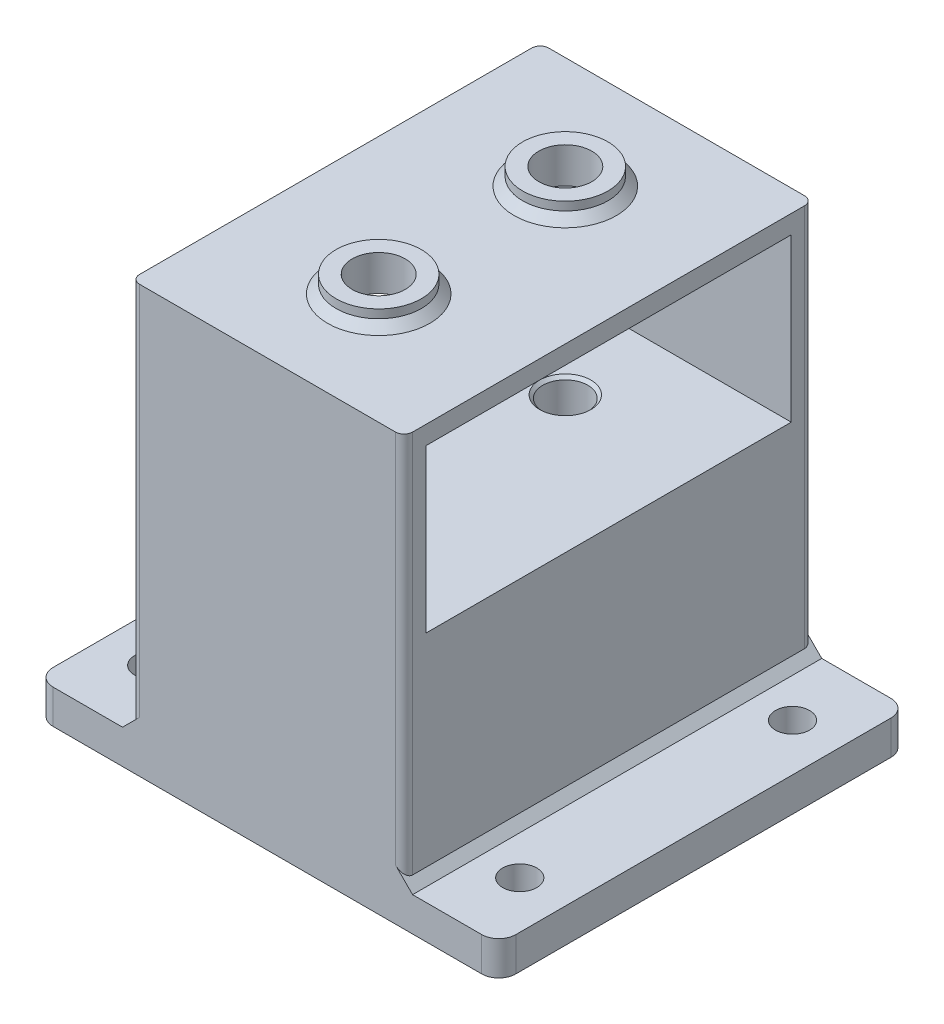
SolidWorks part; units mm, degrees
ref_plane "前视基准面" through (0, 0, 0) normal (0, 0, 1) x (1, 0, 0)
ref_plane "上视基准面" through (0, 0, 0) normal (0, 1, 0) x (1, 0, 0)
ref_plane "右视基准面" through (0, 0, 0) normal (1, 0, 0) x (0, 0, -1)
other "Configuration Table"
sketch "草图1" plane through (0, 370, 0) normal (0, 1, 0) x (1, 0, 0)
  line L1 (-1100, 120) -> (-878.5828, 120)
  line L2 (-1100, 120) -> (-1100, -120)
  line L3 (-1100, -120) -> (-878.5828, -120)
  line L4 (-878.5828, 120) -> (-878.5828, -120)
extrude "凸台-拉伸1" add sketch "草图1" along normal up to surface (20 mm away)
sketch "草图2" plane through (0, 390, 0) normal (0, 1, 0) x (1, 0, 0)
  line L0 (-878.5828, 120) -> (-1100, 120) construction
  line L1 (-1069.2914, 120) -> (-909.1384, 120)
  line L2 (-1069.2914, 120) -> (-1069.2914, -120)
  line L3 (-1069.2914, -120) -> (-909.1384, -120)
  line L4 (-909.1384, 120) -> (-909.1384, -120)
  line L5 (-1069.2914, 120) -> (-1069.2914, -120) construction
  line L6 (-1100, -120) -> (-878.5828, -120) construction
extrude "凸台-拉伸2" add sketch "草图2" along normal up to surface (230 mm away)
sketch "草图3" plane through (-1069.2914, 0, 0) normal (-1, 0, 0) x (0, 0, 1)
  line L1 (-107.105, 609.15) -> (107.105, 609.15)
  line L2 (-107.105, 609.15) -> (-107.105, 513.97)
  line L3 (-107.105, 513.97) -> (107.105, 513.97)
  line L4 (107.105, 609.15) -> (107.105, 513.97)
extrude "切除-拉伸1" cut sketch "草图3" against normal through all
sketch "草图4" plane through (0, 513.97, 0) normal (0, 1, 0) x (1, 0, 0)
  circle A0 centre (-989.2914, 54.73) radius 15.5621
  circle A1 centre (-989.2914, -54.73) radius 15.5621
  point P7 (-989.2914, 54.73)
  point P8 (-989.2914, -54.73)
hole_wizard "M30 螺纹孔1" positions "草图8" profile "草图10" tap size "M30" standard "GB"
sketch "草图8" plane through (0, 513.97, 0) normal (0, 1, 0) x (1, 0, 0)
  point P0 (-989.2914, 54.73)
  point P4 (-989.2914, -54.73)
sketch "草图10" plane through (-989.2914, 513.97, -54.73) normal (1, 0, 0) x (0, 0, 1)
  line L0 (0, 0) -> (0, 57.9614)
  line L1 (0, 57.9614) -> (13.25, 50)
  line L2 (13.25, 50) -> (13.25, 1.775)
  line L3 (13.25, 1.775) -> (15.025, 0)
  line L5 (15.025, 0) -> (0, 0)
  line L6 (-13.25, 1.775) -> (-15.025, 0) construction
  line L10 (0, 57.9614) -> (-13.25, 50) construction
  line L11 (0, -6.35) -> (0, 107.95) construction
  dimension "螺纹孔钻头直径" = 26.5
  dimension "螺纹孔钻头深度" = 50
  dimension "近端锥形沉头孔直径" = 30.05
  dimension "近端锥形沉头孔角度" = 90
  dimension "导头角度" = 118
cosmetic thread "孔螺蚊线1" parameters "D1"=50, "D2"=30
cosmetic thread "孔螺蚊线2" parameters "D1"=50, "D2"=30
sketch "草图11" plane through (0, 620, 0) normal (0, 1, 0) x (1, 0, 0)
  circle A0 centre (-989.2914, 54.73) radius 15.5621
  circle A1 centre (-989.2914, -54.73) radius 15.5621
extrude "切除-拉伸3" cut sketch "草图11" against normal blind 20
sketch "草图12" plane through (0, 620, 0) normal (0, 1, 0) x (1, 0, 0)
  circle A0 centre (-989.2914, 54.73) radius 25
  circle A1 centre (-989.2914, -54.73) radius 25
  dimension "D1" = 50
  dimension "D2" = 50
extrude "凸台-拉伸3" add sketch "草图12" along normal blind 10
sketch "草图13" plane through (0, 630, 0) normal (0, 1, 0) x (1, 0, 0)
  circle A0 centre (-989.2914, 54.73) radius 15.5621
  circle A1 centre (-989.2914, -54.73) radius 15.5621
extrude "切除-拉伸4" cut sketch "草图13" along normal mid plane 59
sketch "草图14" plane through (0, 370, 0) normal (0, -1, 0) x (1, 0, 0)
  line L0 (-878.5828, -120) -> (-1100, -120) construction
  line L1 (-1100, 120) -> (-1125, 120)
  line L2 (-1100, 120) -> (-1100, -120)
  line L3 (-1100, -120) -> (-1125, -120)
  line L4 (-1125, 120) -> (-1125, -120)
  line L5 (-1100, 120) -> (-878.5828, 120) construction
  line L6 (-878.5828, 120) -> (-853.5828, 120)
  line L7 (-878.5828, 120) -> (-878.5828, -120)
  line L8 (-878.5828, -120) -> (-853.5828, -120)
  line L9 (-853.5828, 120) -> (-853.5828, -120)
  line L10 (-878.5828, 120) -> (-878.5828, -120) construction
  dimension "D1" = 25
  dimension "D2" = 25
extrude "凸台-拉伸4" add sketch "草图14" against normal up to surface (20 mm away) up to face at (-1084.6457, 390, 0)
sketch "草图15" plane through (0, 390, 0) normal (0, 1, 0) x (1, 0, 0)
  line L0 (-1097.1457, 120) -> (-1097.1457, -120) construction
  line L1 (-1069.2914, 120) -> (-1125, 120) construction
  line L2 (-1125, -120) -> (-1069.2914, -120) construction
  circle A0 centre (-1097.1457, -80) radius 10
  circle A1 centre (-1097.1457, 80) radius 10
  dimension "D1" = 20
  dimension "D2" = 20
  dimension "D3" = 40
  dimension "D4" = 40
extrude "切除-拉伸5" cut sketch "草图15" against normal mid plane 50
ref_plane "基准面1" through (-989.2149, 0, 0) normal (-1, 0, 0) x (0, 0, 1)
mirror "镜向1" about plane through (-989.2149, 0, 0) normal (-1, 0, 0) of "切除-拉伸5"
chamfer "倒角1" distance 5 angle 45 4 edges at (-1069.2914, 390, 0) (-909.1384, 390, 0) (-989.2914, 620, -29.73) (-989.2914, 620, 79.73)
fillet "圆角1" radius 10 4 edges at (-853.5828, 380, 120) (-853.5828, 380, -120) (-1125, 380, -120) (-1125, 380, 120)
fillet "圆角2" radius 5 4 edges at (-1069.2914, 507.5, 120) (-1069.2914, 507.5, -120) (-909.1384, 507.5, -120) (-909.1384, 507.5, 120)
ref_plane "基准面2" through (0, 0, 0) normal (0, 0, -1) x (-1, 0, 0)
